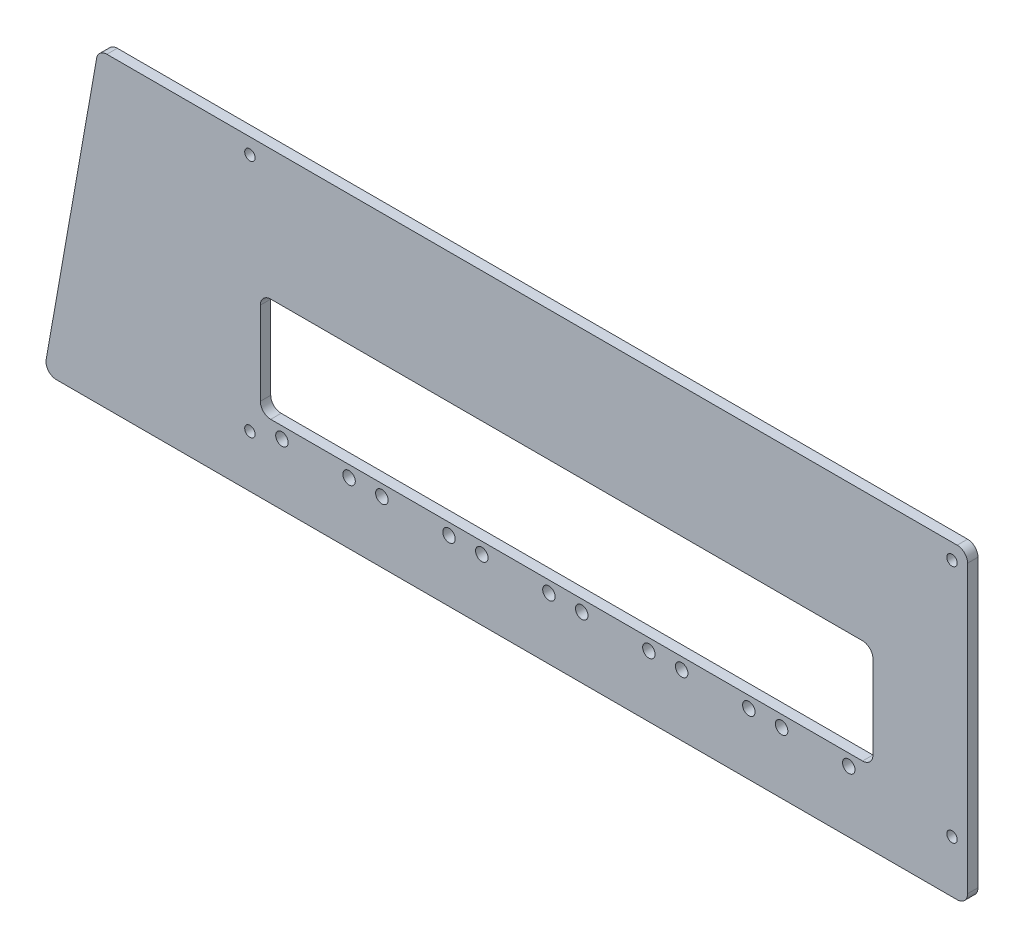
SolidWorks part; units mm, degrees
ref_plane "Front Plane" through (0, 0, 0) normal (0, 0, 1) x (1, 0, 0)
ref_plane "Top Plane" through (0, 0, 0) normal (0, 1, 0) x (1, 0, 0)
ref_plane "Right Plane" through (0, 0, 0) normal (1, 0, 0) x (0, 0, -1)
sketch "Sketch1" plane through (0, 0, 0) normal (0, 0, 1) x (1, 0, 0)
  line L0 (68.1647, -23.6199) -> (-749.2353, -23.6199) construction
  line L1 (68.1647, -23.6199) -> (68.1647, 436.3801)
  line L2 (48.1647, -23.6199) -> (48.1647, 436.3801)
  line L3 (-541.4353, -23.6199) -> (-541.4353, 436.3801)
  line L4 (-561.4353, -23.6199) -> (-561.4353, 436.3801)
  line L5 (-739.2353, -23.6199) -> (-739.2353, 436.3801)
  line L6 (-749.2353, -23.6199) -> (-749.2353, 436.3801)
  line L7 (68.1647, -23.6199) -> (68.1647, 199.2967) construction
  line L8 (68.1647, 436.3801) -> (-749.2353, 436.3801) construction
  line L9 (68.1647, -23.6199) -> (-749.2353, -23.6199) construction
  line L10 (-326.0325, 436.3801) -> (-346.4221, 436.3801) construction
  line L11 (-749.2353, -23.6199) -> (-749.2353, 214.2505) construction
  line L12 (-326.0325, 436.3801) -> (-326.0325, 436.3801) construction
  line L13 (-346.4221, 436.3801) -> (-346.4221, 436.3801) construction
  line L14 (-551.4353, -23.6199) -> (-551.4353, 436.3801) construction
  line L16 (58.1647, -23.6199) -> (58.1647, 436.3801) construction
sketch "Sketch2" plane through (0, 0, 0) normal (0, 0, 1) x (1, 0, 0)
  line L0 (-737.3178, -23.6199) -> (127.9647, -23.6199)
  line L1 (-531.4353, 46.3801) -> (37.0646, 46.3801)
  line L2 (137.9647, 261.3801) -> (137.9647, -13.6199)
  line L3 (127.9647, 271.3801) -> (-688.8278, 271.3801)
  line L4 (-747.1658, -11.8834) -> (-698.6759, 263.1166)
  line L5 (47.0646, 136.3801) -> (47.0646, 56.3801)
  line L6 (-441.4353, 146.3801) -> (-96.8353, 146.3801) construction
  line L7 (-541.4353, 56.3801) -> (-541.4353, 136.3801)
  line L8 (-665.8125, 46.3801) -> (-638.4819, 201.3801) construction
  line L9 (-737.3178, -23.6199) -> (63.1647, -23.6199) construction
  line L10 (3.1647, 201.3801) -> (-638.4819, 201.3801) construction
  line L11 (-665.8125, 46.3801) -> (3.1647, 46.3801) construction
  line L12 (3.1647, 201.3801) -> (3.1647, 46.3801) construction
  line L13 (-531.4353, 146.3801) -> (37.0646, 146.3801)
  line L14 (-541.4353, 56.3801) -> (-541.4353, 191.3801) construction
  line L15 (-441.4353, 146.3801) -> (-441.4353, 191.3801) construction
  line L16 (-96.8353, 191.3801) -> (-96.8353, 146.3801) construction
  line L17 (3.1647, 191.3801) -> (3.1647, 56.3801) construction
  line L18 (-520.6853, 35.3801) -> (-456.1853, 35.3801) construction
  line L19 (73.1647, 256.3801) -> (73.1647, -13.6199) construction
  line L20 (58.1647, 271.3801) -> (-688.8278, 271.3801) construction
  line L21 (-435.4353, 65.3801) -> (-435.4353, 51.3801) construction
  line L22 (-349.4353, 65.3801) -> (-349.4353, 51.3801) construction
  line L23 (-349.4353, 65.3801) -> (-435.4353, 65.3801) construction
  line L24 (-392.4353, 51.3801) -> (-392.4353, 40.877) construction
  line L25 (-349.4353, 51.3801) -> (-435.4353, 51.3801) construction
  line L26 (-360.1853, 35.3801) -> (-424.6853, 35.3801) construction
  line L27 (-344.4353, 58.3801) -> (-344.4353, 26.3801) construction
  line L28 (-440.4353, 58.3801) -> (-440.4353, 26.3801) construction
  line L29 (-531.4353, 51.3801) -> (-445.4353, 51.3801) construction
  line L30 (-243.4353, 65.3801) -> (-243.4353, 51.3801) construction
  line L31 (-488.4353, 51.3801) -> (-488.4353, 40.877) construction
  line L32 (-157.4353, 65.3801) -> (-157.4353, 51.3801) construction
  line L33 (-157.4353, 65.3801) -> (-243.4353, 65.3801) construction
  line L34 (-200.4353, 51.3801) -> (-200.4353, 40.877) construction
  line L35 (-157.4353, 51.3801) -> (-243.4353, 51.3801) construction
  line L36 (-248.4353, 58.3801) -> (-248.4353, 26.3801) construction
  line L37 (-328.6853, 35.3801) -> (-264.1853, 35.3801) construction
  line L38 (-531.4353, 65.3801) -> (-445.4353, 65.3801) construction
  line L39 (-531.4353, 65.3801) -> (-531.4353, 51.3801) construction
  line L40 (-445.4353, 65.3801) -> (-445.4353, 51.3801) construction
  line L41 (-339.4353, 51.3801) -> (-253.4353, 51.3801) construction
  line L42 (-296.4353, 51.3801) -> (-296.4353, 40.877) construction
  line L43 (-339.4353, 65.3801) -> (-253.4353, 65.3801) construction
  line L44 (-339.4353, 65.3801) -> (-339.4353, 51.3801) construction
  line L45 (-253.4353, 65.3801) -> (-253.4353, 51.3801) construction
  line L46 (-168.1853, 35.3801) -> (-232.6853, 35.3801) construction
  line L47 (-152.4353, 58.3801) -> (-152.4353, 26.3801) construction
  line L48 (-136.6853, 35.3801) -> (-72.1853, 35.3801) construction
  line L49 (122.9647, 256.3801) -> (186.9251, 256.3801) construction
  line L50 (37.0646, 65.3801) -> (-48.9354, 65.3801) construction
  line L51 (37.0646, 65.3801) -> (47.0646, 65.3801) construction
  line L52 (37.0646, 51.3801) -> (-48.9354, 51.3801) construction
  line L53 (-531.4353, 46.3801) -> (-6.8353, 46.3801) construction
  line L54 (-8.4353, 51.3801) -> (-8.4353, 40.877) construction
  line L55 (-48.9354, 65.3801) -> (-48.9354, 51.3801) construction
  line L56 (-147.4353, 51.3801) -> (-61.4353, 51.3801) construction
  line L57 (-104.4353, 51.3801) -> (-104.4353, 40.877) construction
  line L58 (-147.4353, 65.3801) -> (-61.4353, 65.3801) construction
  line L59 (-147.4353, 65.3801) -> (-147.4353, 51.3801) construction
  line L60 (-61.4353, 65.3801) -> (-61.4353, 51.3801) construction
  line L61 (39.5647, 58.3801) -> (39.5647, 26.3801) construction
  line L63 (37.0646, 65.3801) -> (37.0646, 51.3801) construction
  line L64 (23.8147, 35.3801) -> (-40.6853, 35.3801) construction
  circle A0 centre (122.9647, 256.3801) radius 5
  circle A1 centre (-520.6853, 35.3801) radius 6
  circle A2 centre (122.9647, 26.3801) radius 5
  circle A3 centre (-551.4353, 256.3801) radius 5
  circle A4 centre (122.9647, 256.3801) radius 15 construction
  circle A5 centre (-551.4353, 256.3801) radius 15 construction
  arc A6 (127.9647, 271.3801) -> (137.9647, 261.3801) centre (127.9647, 261.3801) cw
  arc A7 (127.9647, -23.6199) -> (137.9647, -13.6199) centre (127.9647, -13.6199) ccw
  arc A8 (-737.3178, -23.6199) -> (-747.1658, -11.8834) centre (-737.3178, -13.6199) cw
  arc A9 (-688.8278, 271.3801) -> (-698.6759, 263.1166) centre (-688.8278, 261.3801) ccw
  arc A10 (47.0646, 136.3801) -> (37.0646, 146.3801) centre (37.0646, 136.3801) ccw
  arc A11 (37.0646, 46.3801) -> (47.0646, 56.3801) centre (37.0646, 56.3801) ccw
  arc A12 (-541.4353, 56.3801) -> (-531.4353, 46.3801) centre (-531.4353, 56.3801) ccw
  circle A13 centre (-456.1853, 35.3801) radius 6
  arc A14 (-638.4819, 201.3801) -> (-638.4819, 201.3801) centre (-638.4819, 201.3801) ccw construction
  arc A15 (-665.8125, 46.3801) -> (-665.8125, 46.3801) centre (-665.8125, 46.3801) cw construction
  arc A16 (3.1647, 201.3801) -> (3.1647, 201.3801) centre (3.1647, 201.3801) cw construction
  arc A17 (3.1647, 46.3801) -> (3.1647, 46.3801) centre (3.1647, 46.3801) ccw construction
  arc A18 (-531.4353, 146.3801) -> (-541.4353, 136.3801) centre (-531.4353, 136.3801) ccw
  arc A19 (-441.4353, 146.3801) -> (-441.4353, 146.3801) centre (-441.4353, 146.3801) ccw construction
  arc A20 (-96.8353, 146.3801) -> (-96.8353, 146.3801) centre (-96.8353, 146.3801) ccw construction
  circle A21 centre (-424.6853, 35.3801) radius 6
  circle A22 centre (-360.1853, 35.3801) radius 6
  arc A23 (63.1647, -23.6199) -> (73.1647, -13.6199) centre (63.1647, -13.6199) ccw construction
  arc A24 (58.1647, 271.3801) -> (73.1647, 256.3801) centre (58.1647, 256.3801) cw construction
  circle A25 centre (-328.6853, 35.3801) radius 6
  circle A26 centre (-264.1853, 35.3801) radius 6
  circle A27 centre (-232.6853, 35.3801) radius 6
  circle A28 centre (-168.1853, 35.3801) radius 6
  circle A29 centre (-136.6853, 35.3801) radius 6
  circle A30 centre (-72.1853, 35.3801) radius 6
  circle A31 centre (-551.4353, 26.3801) radius 5
  circle A32 centre (-40.6853, 35.3801) radius 6
  circle A34 centre (23.8147, 35.3801) radius 6
  arc A35 (-6.8353, 46.3801) -> (3.1647, 56.3801) centre (-6.8353, 56.3801) ccw construction
  point P28 (-749.2353, -23.6199)
  dimension "D1" = 86
  dimension "D3" = 10
  dimension "D4" = 10
  dimension "D5" = 10
  dimension "D6" = 10
  dimension "D7" = 10
  dimension "D8" = 280
  dimension "D2" = 230
sketch "microtiterplate" plane through (0, 0, 0) normal (0, 0, 1) x (1, 0, 0)
  line L1 (-531.4353, 71.3801) -> (-442.5353, 71.3801) construction
  line L2 (-531.4353, 71.3801) -> (-531.4353, 56.3801) construction
  line L3 (-531.4353, 56.3801) -> (-442.5353, 56.3801) construction
  line L4 (-442.5353, 71.3801) -> (-442.5353, 56.3801) construction
extrude "Boss-Extrude1" add sketch "Sketch2" along normal blind 10
sketch "Sketch4" plane through (0, 0, 0) normal (0, 0, 1) x (1, 0, 0)
  line L0 (-532.9779, 100.6337) -> (-532.9779, 94.2837)
  line L1 (-508.9779, 118.6087) -> (-461.4779, 118.6087)
  line L2 (-508.9779, 118.6087) -> (-508.9779, 100.6337)
  line L3 (-508.9779, 76.3087) -> (-461.4779, 76.3087)
  line L4 (-461.4779, 118.6087) -> (-461.4779, 100.6337)
  line L5 (-508.9779, 100.6337) -> (-532.9779, 100.6337)
  line L6 (-508.9779, 94.2837) -> (-532.9779, 94.2837)
  line L7 (-451.4779, 100.6337) -> (-451.4779, 94.2837)
  line L8 (-461.4779, 100.6337) -> (-451.4779, 100.6337)
  line L9 (-461.4779, 94.2837) -> (-451.4779, 94.2837)
  line L10 (-461.4779, 94.2837) -> (-461.4779, 76.3087)
  line L11 (-508.9779, 94.2837) -> (-508.9779, 76.3087)
  dimension "D1" = 47.5
  dimension "D2" = 42.3
sketch "NEMA17_positions" plane through (0, 0, 0) normal (0, 0, 1) x (1, 0, 0)
  line L0 (-482.3506, 54.4332) -> (-488.7006, 54.4332)
  line L1 (-464.3756, 30.4332) -> (-464.3756, -17.0668)
  line L2 (-464.3756, 30.4332) -> (-482.3506, 30.4332)
  line L3 (-506.6756, 30.4332) -> (-506.6756, -17.0668)
  line L4 (-464.3756, -17.0668) -> (-482.3506, -17.0668)
  line L5 (-482.3506, 30.4332) -> (-482.3506, 54.4332)
  line L6 (-488.7006, 30.4332) -> (-488.7006, 54.4332)
  line L7 (-482.3506, -27.0668) -> (-488.7006, -27.0668)
  line L8 (-482.3506, -17.0668) -> (-482.3506, -27.0668)
  line L9 (-488.7006, -17.0668) -> (-488.7006, -27.0668)
  line L10 (-488.7006, -17.0668) -> (-506.6756, -17.0668)
  line L11 (-488.7006, 30.4332) -> (-506.6756, 30.4332)
  dimension "D1" = 47.5
  dimension "D2" = 42.3
sketch "Sketch5" plane through (0, 0, 0) normal (0, 0, 1) x (1, 0, 0)
  line L0 (-404.862, 32.5293) -> (-425.436, 32.5293)
  line L1 (-466.584, 57.9293) -> (-425.436, 57.9293)
  line L2 (-466.584, 57.9293) -> (-466.584, 0.7793)
  line L3 (-466.584, 0.7793) -> (-425.436, 0.7793)
  line L4 (-425.436, 57.9293) -> (-425.436, 32.5293)
  line L5 (-404.862, 26.1793) -> (-425.436, 26.1793)
  line L6 (-425.436, 26.1793) -> (-425.436, 0.7793)
  line L7 (-404.862, 32.5293) -> (-404.862, 26.1793)
  line L8 (-404.862, 26.1793) -> (-404.8476, 26.1484)
  dimension "D1" = 57.15
  dimension "D2" = 41.148
sketch "Sketch7" plane through (0, 0, 0) normal (0, 0, 1) x (1, 0, 0)
  line L21 (-435.4353, 65.3801) -> (-435.4353, 51.3801)
  line L22 (-349.4353, 65.3801) -> (-349.4353, 51.3801)
  line L23 (-349.4353, 65.3801) -> (-435.4353, 65.3801)
  line L25 (-349.4353, 51.3801) -> (-435.4353, 51.3801)
  line L29 (-531.4353, 51.3801) -> (-445.4353, 51.3801)
  line L30 (-243.4353, 65.3801) -> (-243.4353, 51.3801)
  line L32 (-157.4353, 65.3801) -> (-157.4353, 51.3801)
  line L33 (-157.4353, 65.3801) -> (-243.4353, 65.3801)
  line L35 (-157.4353, 51.3801) -> (-243.4353, 51.3801)
  line L38 (-531.4353, 65.3801) -> (-445.4353, 65.3801)
  line L39 (-531.4353, 65.3801) -> (-531.4353, 51.3801)
  line L40 (-445.4353, 65.3801) -> (-445.4353, 51.3801)
  line L41 (-339.4353, 51.3801) -> (-253.4353, 51.3801)
  line L43 (-339.4353, 65.3801) -> (-253.4353, 65.3801)
  line L44 (-339.4353, 65.3801) -> (-339.4353, 51.3801)
  line L45 (-253.4353, 65.3801) -> (-253.4353, 51.3801)
  line L56 (-147.4353, 51.3801) -> (-61.4353, 51.3801)
  line L58 (-147.4353, 65.3801) -> (-61.4353, 65.3801)
  line L59 (-147.4353, 65.3801) -> (-147.4353, 51.3801)
  line L60 (-61.4353, 65.3801) -> (-61.4353, 51.3801)
  dimension "D1" = 86
